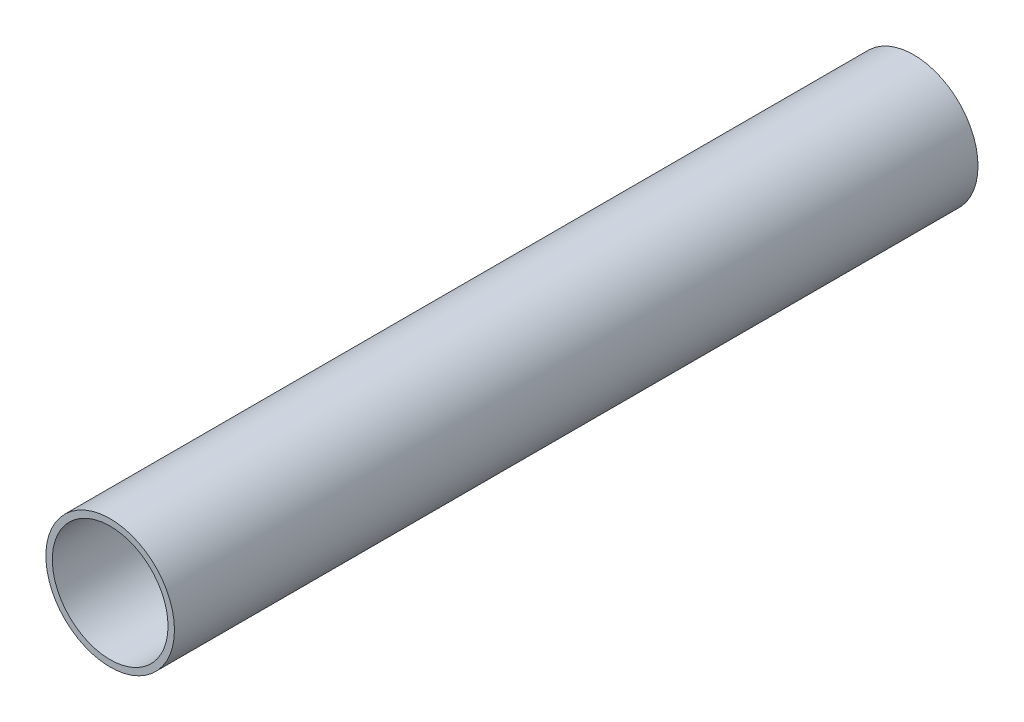
SolidWorks part; units mm, degrees
ref_plane "Front Plane" through (0, 0, 0) normal (0, 0, 1) x (1, 0, 0)
ref_plane "Top Plane" through (0, 0, 0) normal (0, 1, 0) x (1, 0, 0)
ref_plane "Right Plane" through (0, 0, 0) normal (1, 0, 0) x (0, 0, -1)
sketch "Sketch1" plane through (0, 0, 0) normal (0, 0, 1) x (1, 0, 0)
  circle A0 centre (0, 0) radius 18
  circle A1 centre (0, 0) radius 20
  dimension "D1" = 36
  dimension "D2" = 40
extrude "Boss-Extrude1" add sketch "Sketch1" along normal blind 250
